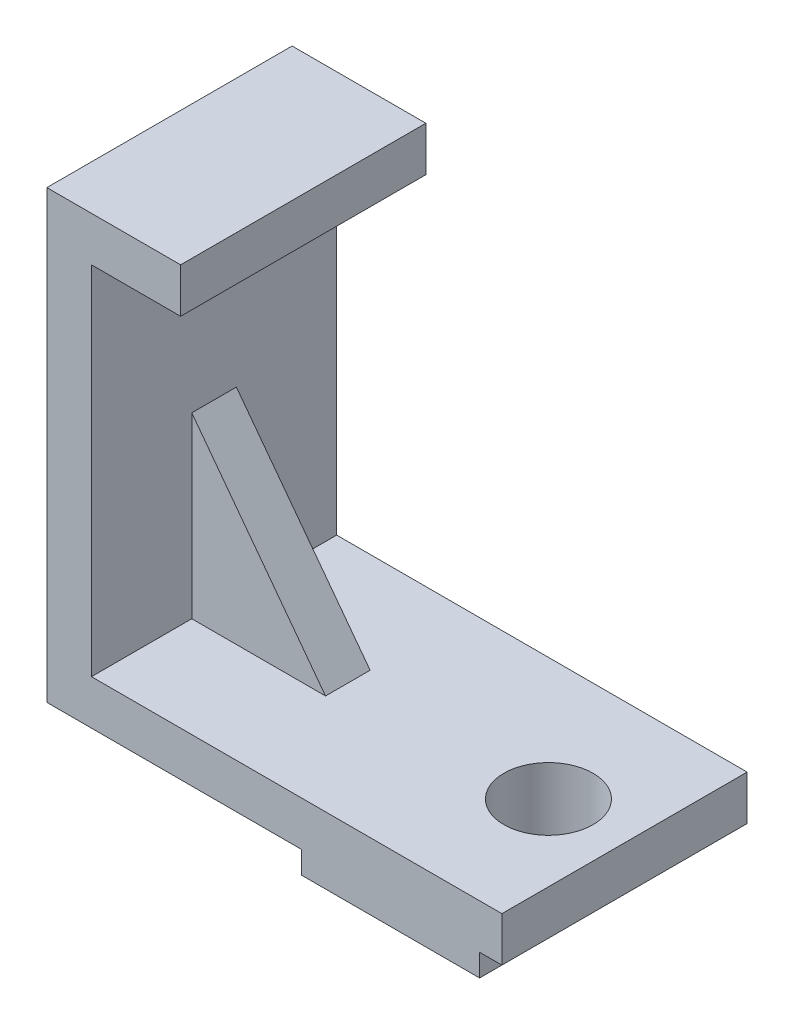
SolidWorks part; units mm, degrees
ref_plane "Front Plane" through (0, 0, 0) normal (0, 0, 1) x (1, 0, 0)
ref_plane "Top Plane" through (0, 0, 0) normal (0, 1, 0) x (1, 0, 0)
ref_plane "Right Plane" through (0, 0, 0) normal (1, 0, 0) x (0, 0, -1)
sketch "Sketch1" plane through (0, 0, 0) normal (0, 0, 1) x (1, 0, 0)
  line L0 (-27.0552, 21.2577) -> (-27.0552, 31.2577)
  line L1 (-27.0552, 31.2577) -> (-57.0552, 31.2577)
  line L2 (-57.0552, 31.2577) -> (-57.0552, -68.7423)
  line L3 (-57.0552, -68.7423) -> (0, -68.7423)
  line L4 (0, -68.7423) -> (0, -73.7423)
  line L5 (0, -73.7423) -> (40, -73.7423)
  line L6 (40, -73.7423) -> (40, -68.7423)
  line L7 (40, -68.7423) -> (45, -68.7423)
  line L8 (45, -68.7423) -> (45, -58.7423)
  line L9 (45, -58.7423) -> (-47.0552, -58.7423)
  line L10 (-47.0552, -58.7423) -> (-47.0552, 21.2577)
  line L11 (-47.0552, 21.2577) -> (-27.0552, 21.2577)
  dimension "D1" = 100
  dimension "D2" = 10
  dimension "D3" = 5
  dimension "D4" = 5
  dimension "D5" = 40
  dimension "D6" = 10
  dimension "D7" = 10
  dimension "D8" = 20
extrude "Boss-Extrude1" add sketch "Sketch1" along normal blind 55
ref_plane "Plane1" through (0, 0, 27.5) normal (0, 0, 1) x (1, 0, 0)
sketch "Sketch2" plane through (0, 0, 27.5) normal (0, 0, 1) x (1, 0, 0)
  line L0 (-47.0552, -18.7423) -> (-17.0552, -58.7423)
  line L3 (-47.0552, -58.7423) -> (-47.0552, 21.2577) construction
  line L4 (45, -58.7423) -> (-47.0552, -58.7423) construction
  dimension "D1" = 30
  dimension "D2" = 40
rib "Rib1" sketch "Sketch2" sketch "Sketch2" thickness 10 extrusion direction parallel to sketch draft on no parameters "D1"=10
sketch "Sketch3" plane through (0, -58.7423, 0) normal (0, 1, 0) x (1, 0, 0)
  circle A0 centre (27.9448, -27.5) radius 10
  dimension "D2" = 20
extrude "Cut-Extrude1" cut sketch "Sketch3" against normal through all
